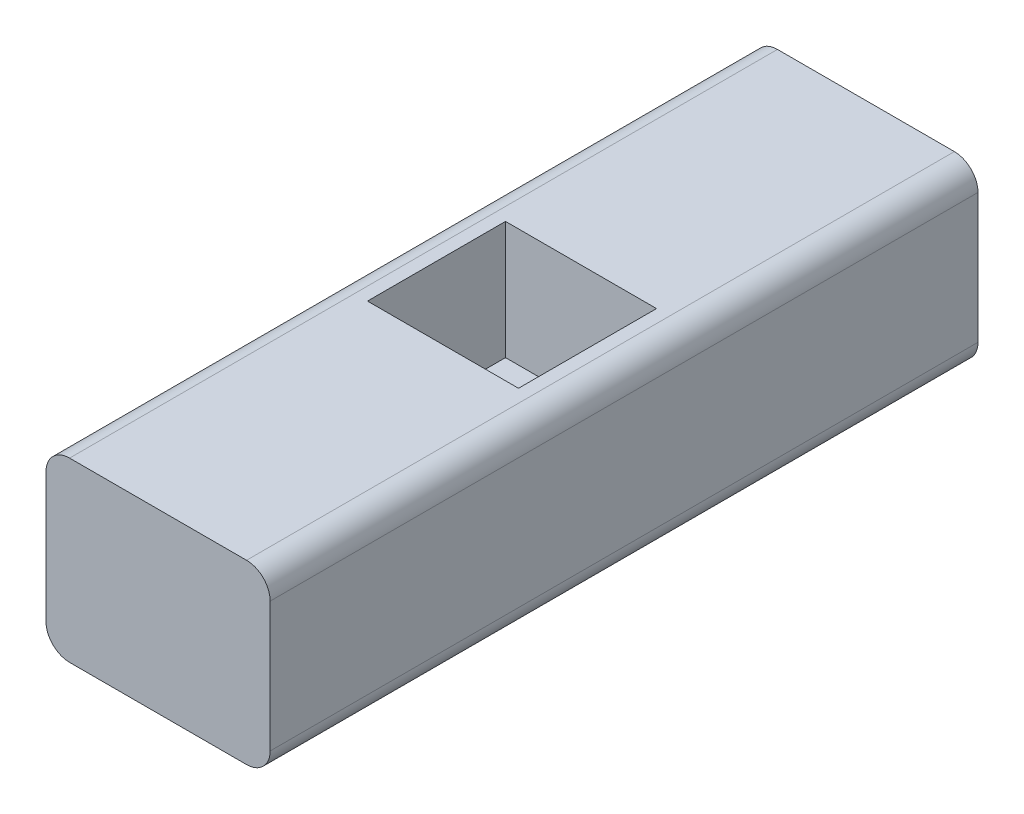
SolidWorks part; units mm, degrees
ref_plane "Front Plane" through (0, 0, 0) normal (0, 0, 1) x (1, 0, 0)
ref_plane "Top Plane" through (0, 0, 0) normal (0, 1, 0) x (1, 0, 0)
ref_plane "Right Plane" through (0, 0, 0) normal (1, 0, 0) x (0, 0, -1)
sketch "Sketch4" plane through (0, 0, 0) normal (0, 0, 1) x (1, 0, 0)
  line L1 (-15, -15) -> (15, -15)
  line L2 (-19, -11) -> (-19, 11)
  line L3 (-15, 15) -> (15, 15)
  line L4 (19, -11) -> (19, 11)
  line L5 (-19, -15) -> (19, 15) construction
  line L6 (-19, 15) -> (19, -15) construction
  arc A0 (15, -15) -> (19, -11) centre (15, -11) ccw
  arc A1 (-15, -15) -> (-19, -11) centre (-15, -11) cw
  arc A2 (-19, 11) -> (-15, 15) centre (-15, 11) cw
  arc A3 (15, 15) -> (19, 11) centre (15, 11) cw
  point P0 (0, 0)
  dimension "D3" = 4
  dimension "D1" = 38
  dimension "D2" = 30
extrude "Boss-Extrude2" add sketch "Sketch4" along normal blind 120
sketch "Sketch5" plane through (0, 0, 0) normal (1, 0, 0) x (0, 0, -1)
  line L0 (-120, -15) -> (0, -15) construction
  line L1 (-48.3, -5) -> (-71.7, -5)
  line L2 (-48.3, -5) -> (-48.3, 24)
  line L3 (-48.3, 24) -> (-71.7, 24)
  line L4 (-71.7, -5) -> (-71.7, 24)
  line L5 (-48.3, -5) -> (-71.7, 24) construction
  line L6 (-48.3, 24) -> (-71.7, -5) construction
  line L7 (-60, 11) -> (-60, -15) construction
  line L8 (-120, 11) -> (0, 11) construction
  point P0 (-60, 9.5)
  dimension "D1" = 23.4
  dimension "D2" = 29
  dimension "D3" = 10
extrude "Cut-Extrude1" cut sketch "Sketch5" against normal blind 12.8 and the other way blind 12.8
